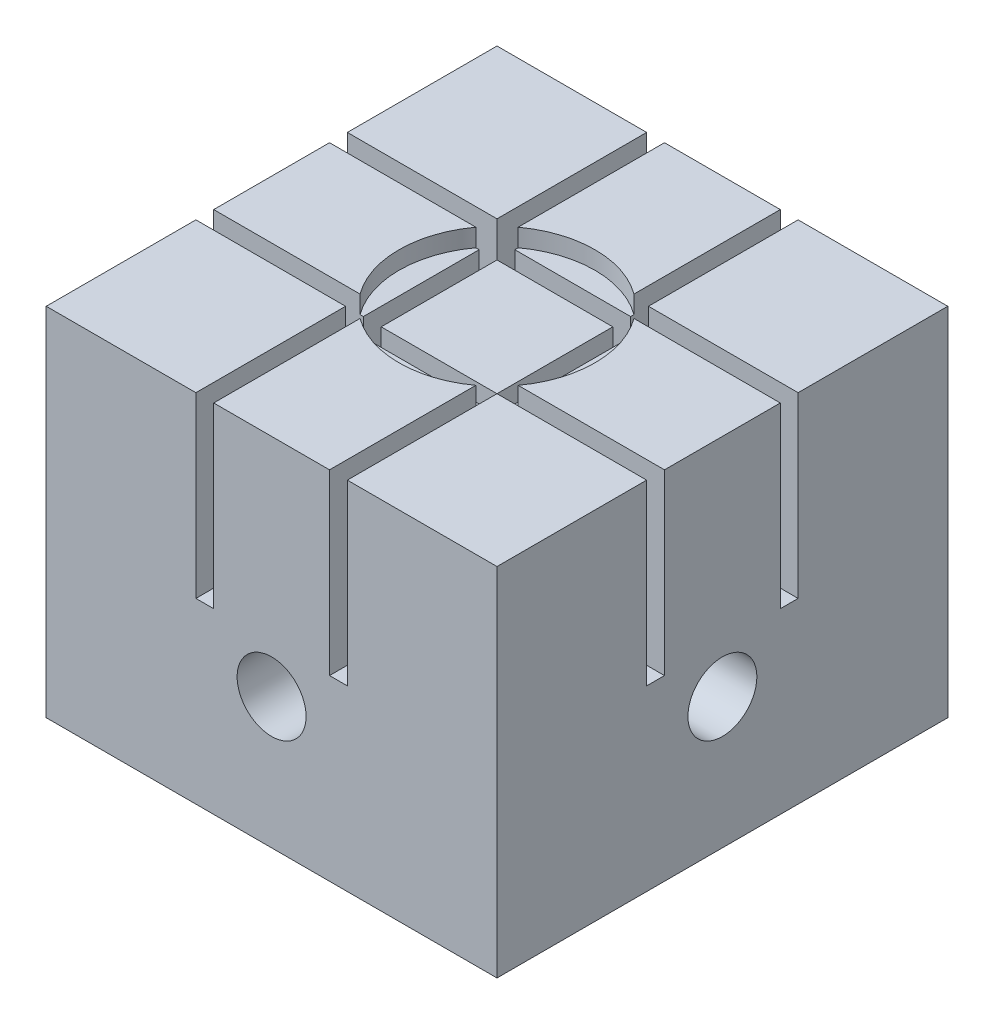
SolidWorks part; units mm, degrees
ref_plane "Front Plane" through (0, 0, 0) normal (0, 0, 1) x (1, 0, 0)
ref_plane "Top Plane" through (0, 0, 0) normal (0, 1, 0) x (1, 0, 0)
ref_plane "Right Plane" through (0, 0, 0) normal (1, 0, 0) x (0, 0, -1)
sketch "Sketch1" plane through (0, 0, 0) normal (0, 0, 1) x (1, 0, 0)
  line L1 (-16.0655, 16.0655) -> (16.0655, 16.0655)
  line L2 (-16.0655, 16.0655) -> (-16.0655, -9.3345)
  line L3 (-16.0655, -9.3345) -> (16.0655, -9.3345)
  line L4 (16.0655, 16.0655) -> (16.0655, -9.3345)
  dimension "D1" = 32.131
  dimension "D2" = 25.4
  dimension "D3" = 16.0655
  dimension "D4" = 16.0655
extrude "Boss-Extrude1" add sketch "Sketch1" along normal blind 32.131
sketch "Sketch2" plane through (0, 16.0655, 0) normal (0, 1, 0) x (1, 0, 0)
  line L0 (16.0655, 0) -> (-16.0655, 0) construction
  line L1 (-5.3975, 0) -> (-4.1275, 0)
  line L2 (-5.3975, 0) -> (-5.3975, -32.131)
  line L3 (-5.3975, -32.131) -> (-4.1275, -32.131)
  line L4 (-4.1275, 0) -> (-4.1275, -32.131)
  line L5 (4.1275, 0) -> (5.3975, 0)
  line L6 (4.1275, 0) -> (4.1275, -32.131)
  line L7 (4.1275, -32.131) -> (5.3975, -32.131)
  line L8 (5.3975, 0) -> (5.3975, -32.131)
  line L9 (16.0655, -32.131) -> (-16.0655, -32.131) construction
  line L10 (-16.0655, -32.131) -> (-16.0655, 0) construction
  line L11 (-16.0655, -10.668) -> (16.0655, -10.668)
  line L12 (-16.0655, -10.668) -> (-16.0655, -11.938)
  line L13 (-16.0655, -11.938) -> (16.0655, -11.938)
  line L14 (16.0655, -10.668) -> (16.0655, -11.938)
  line L15 (-16.0655, -20.193) -> (16.0655, -20.193)
  line L16 (-16.0655, -20.193) -> (-16.0655, -21.463)
  line L17 (-16.0655, -21.463) -> (16.0655, -21.463)
  line L18 (16.0655, -20.193) -> (16.0655, -21.463)
  line L19 (16.0655, -32.131) -> (16.0655, 0) construction
  dimension "D1" = 1.27
  dimension "D2" = 20.193
  dimension "D3" = 20.193
  dimension "D4" = 20.193
  dimension "D5" = 20.193
extrude "Cut-Extrude1" cut sketch "Sketch2" against normal blind 12.7 contours L6 L7 L8 L5 | L15 L18 L17 L16 | L2 L3 L4 L1 | L11 L14 L13 L12
sketch "Sketch3" plane through (0, 16.0655, 0) normal (0, 1, 0) x (1, 0, 0)
  line L0 (-16.0655, -20.193) -> (-16.0655, -11.938) construction
  circle A0 centre (0, -16.0655) radius 6.985
  point P2 (-16.0655, -16.0655)
  dimension "D3" = 13.97
  dimension "D1" = 16.0655
  dimension "D2" = 16.0655
extrude "Cut-Extrude2" cut sketch "Sketch3" against normal blind 1.27
hole_wizard "#10 (0.1935) Diameter Hole6" positions "Sketch17" profile "Sketch16" hole size "#10" standard "ANSI Inch"
sketch "Sketch17" plane through (0, 0, 32.131) normal (0, 0, 1) x (1, 0, 0)
  point P0 (0, 0)
sketch "Sketch16" plane through (0, 0, 32.131) normal (1, 0, 0) x (0, -1, 0)
  line L0 (0, 0) -> (0, 9.0966)
  line L1 (0, 9.0966) -> (2.4574, 7.62)
  line L2 (2.4574, 7.62) -> (2.4574, 0)
  line L5 (2.4574, 0) -> (0, 0)
  line L10 (0, 9.0966) -> (-2.4574, 7.62) construction
  line L11 (0, -6.35) -> (0, 107.95) construction
  dimension "Hole Dia." = 4.9149
  dimension "Hole Depth" = 7.62
  dimension "Drill Angle" = 118
hole_wizard "#10 (0.1935) Diameter Hole7" positions "Sketch19" profile "Sketch18" hole size "#10" standard "ANSI Inch"
sketch "Sketch19" plane through (0, 0, 0) normal (0, 0, -1) x (-1, 0, 0)
  point P0 (0, 0)
sketch "Sketch18" plane through (0, 0, 0) normal (1, 0, 0) x (0, 1, 0)
  line L0 (0, 0) -> (0, 9.0966)
  line L1 (0, 9.0966) -> (2.4574, 7.62)
  line L2 (2.4574, 7.62) -> (2.4574, 0)
  line L5 (2.4574, 0) -> (0, 0)
  line L10 (0, 9.0966) -> (-2.4574, 7.62) construction
  line L11 (0, -6.35) -> (0, 107.95) construction
  dimension "Hole Dia." = 4.9149
  dimension "Hole Depth" = 7.62
  dimension "Drill Angle" = 118
ref_plane "Plane5" through (0, 0, 16.0655) normal (0, 0, 1) x (1, 0, 0)
hole_wizard "#10 (0.1935) Diameter Hole8" positions "Sketch22" profile "Sketch20" hole size "#10" standard "ANSI Inch"
sketch "Sketch22" plane through (16.0655, 0, 0) normal (1, 0, 0) x (0, 0, -1)
  line L0 (-16.0655, 13.97) -> (-16.0655, -13.97) construction
  point P0 (-16.0655, 0)
sketch "Sketch20" plane through (16.0655, 0, 16.0655) normal (0, 1, 0) x (0, 0, -1)
  line L0 (0, 0) -> (0, 9.0966)
  line L1 (0, 9.0966) -> (2.4574, 7.62)
  line L2 (2.4574, 7.62) -> (2.4574, 0)
  line L5 (2.4574, 0) -> (0, 0)
  line L10 (0, 9.0966) -> (-2.4574, 7.62) construction
  line L11 (0, -6.35) -> (0, 107.95) construction
  dimension "Hole Dia." = 4.9149
  dimension "Hole Depth" = 7.62
  dimension "Drill Angle" = 118
hole_wizard "#10 (0.1935) Diameter Hole9" positions "Sketch24" profile "Sketch23" hole size "#10" standard "ANSI Inch"
sketch "Sketch24" plane through (-16.0655, 0, 0) normal (-1, 0, 0) x (0, 0, 1)
  line L0 (16.0655, -13.97) -> (16.0655, 13.97) construction
  point P0 (16.0655, 0)
sketch "Sketch23" plane through (-16.0655, 0, 16.0655) normal (0, 1, 0) x (0, 0, 1)
  line L0 (0, 0) -> (0, 9.0966)
  line L1 (0, 9.0966) -> (2.4574, 7.62)
  line L2 (2.4574, 7.62) -> (2.4574, 0)
  line L5 (2.4574, 0) -> (0, 0)
  line L10 (0, 9.0966) -> (-2.4574, 7.62) construction
  line L11 (0, -6.35) -> (0, 107.95) construction
  dimension "Hole Dia." = 4.9149
  dimension "Hole Depth" = 7.62
  dimension "Drill Angle" = 118
